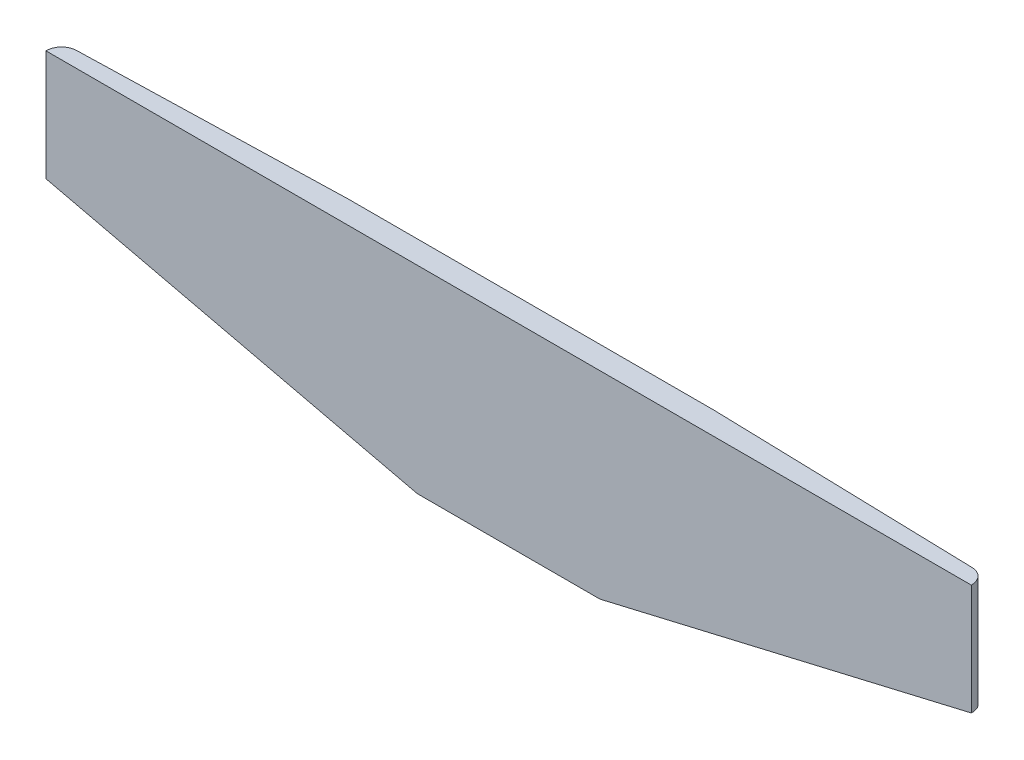
SolidWorks part; units mm, degrees
material "Alloy Steel"
ref_plane "Front Plane" through (0, 0, 0) normal (0, 0, 1) x (1, 0, 0)
ref_plane "Top Plane" through (0, 0, 0) normal (0, 1, 0) x (1, 0, 0)
ref_plane "Right Plane" through (0, 0, 0) normal (1, 0, 0) x (0, 0, -1)
sketch "Sketch1" plane through (0, 0, 0) normal (0, 0, 1) x (1, 0, 0)
  line L0 (193.04, 0) -> (193.04, -82.55) construction
  line L1 (0, 0) -> (386.08, 0)
  line L2 (0, 0) -> (0, -46.228)
  line L3 (0, -46.228) -> (386.08, -46.228) construction
  line L4 (386.08, 0) -> (386.08, -46.228)
  line L5 (154.94, -46.228) -> (231.14, -46.228) construction
  line L6 (154.94, -46.228) -> (154.94, -82.55) construction
  line L7 (154.94, -82.55) -> (231.14, -82.55)
  line L8 (231.14, -46.228) -> (231.14, -82.55) construction
  line L9 (154.94, -82.55) -> (0, -46.228)
  line L10 (231.14, -82.55) -> (386.08, -46.228)
  dimension "D1" = 386.08
  dimension "D2" = 46.228
  dimension "D3" = 76.2
  dimension "D4" = 82.55
sketch "Sketch2" plane through (0, 0, 0) normal (0, 1, 0) x (1, 0, 0)
  line L0 (0, 0) -> (386.08, 0) construction
  line L1 (0, 0) -> (386.08, 0)
  line L2 (386.08, 0) -> (386.08, 6.35)
  line L3 (0, 6.35) -> (116.84, 9.525)
  line L4 (386.08, 6.35) -> (269.24, 9.525)
  line L5 (269.24, 9.525) -> (116.84, 9.525)
  line L6 (193.04, 0) -> (193.04, 9.525)
  line L7 (0, 0) -> (0, 6.35)
  dimension "D1" = 6.35
  dimension "D2" = 76.2
  dimension "D3" = 9.525
extrude "Boss-Extrude1" add sketch "Sketch2" against normal up to vertex (82.55 mm away) contours L6 L1 L2 L4 L5 | L7 L1 L6 L5 L3 up to point (193.04, -82.55, 0)
extrude "Cut-Extrude1" cut sketch "Sketch1" against normal through all flip side to cut
fillet "Fillet2" radius 6.35 1 edges at (386.08, -23.114, -6.35)
fillet "Fillet3" radius 6.35 1 edges at (0, -23.114, -6.35)
